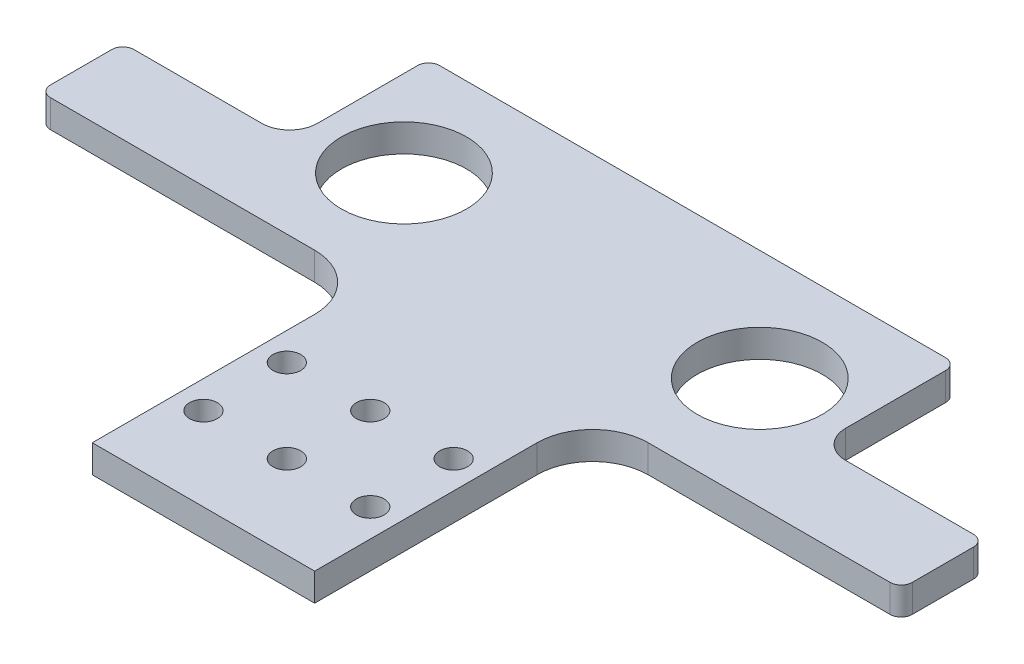
SolidWorks part; units mm, degrees
ref_plane "Front Plane" through (0, 0, 0) normal (0, 0, 1) x (1, 0, 0)
ref_plane "Top Plane" through (0, 0, 0) normal (0, 1, 0) x (1, 0, 0)
ref_plane "Right Plane" through (0, 0, 0) normal (1, 0, 0) x (0, 0, -1)
sketch "Sketch2" plane through (0, 0, 0) normal (0, 1, 0) x (1, 0, 0)
  line L1 (-52.4007, -9.869) -> (68.2493, -9.869)
  line L2 (-52.4007, -9.869) -> (-52.4007, 40.931)
  line L3 (-52.4007, 40.931) -> (68.2493, 40.931)
  line L4 (68.2493, -9.869) -> (68.2493, 40.931)
  line L5 (-52.4007, -9.869) -> (68.2493, 40.931) construction
  line L6 (-52.4007, 40.931) -> (68.2493, -9.869) construction
  point P0 (7.9243, 15.531)
  dimension "D1" = 120.65
  dimension "D2" = 50.8
extrude "Boss-Extrude1" add sketch "Sketch2" along normal blind 6.35
ref_plane "Plane1" through (7.9243, 0, 0) normal (1, 0, 0) x (0, 0, -1)
sketch "Sketch3" plane through (0, 6.35, 0) normal (0, 1, 0) x (1, 0, 0)
  line L0 (7.9243, -3.4925) -> (7.9243, 3.4925) construction
  line L2 (68.2493, 40.931) -> (-52.4007, 40.931) construction
  circle A0 centre (-32.7157, 15.6148) radius 14.2875
  dimension "D1" = 28.575
  dimension "D2" = 40.64
  dimension "D3" = 25.3163
extrude "Cut-Extrude1" cut sketch "Sketch3" against normal blind 6.35 contours A0
mirror "Mirror1" about plane through (7.9243, 0, 0) normal (1, 0, 0) of "Cut-Extrude1"
sketch "Sketch6" plane through (0, 6.35, 0) normal (0, 1, 0) x (1, 0, 0)
  line L0 (-52.4007, 40.931) -> (-52.4007, -9.869) construction
  line L1 (-90.5007, 9.181) -> (-52.4007, 9.181)
  line L2 (-90.5007, 9.181) -> (-90.5007, -9.869)
  line L3 (-90.5007, -9.869) -> (-52.4007, -9.869)
  line L4 (-52.4007, 9.181) -> (-52.4007, -9.869)
  line L5 (-52.4007, -9.869) -> (68.2493, -9.869) construction
  dimension "D1" = 38.1
  dimension "D2" = 0
  dimension "D3" = 0
  dimension "D4" = 19.05
extrude "Boss-Extrude2" add sketch "Sketch6" against normal blind 6.35
mirror "Mirror2" about plane through (7.9243, 0, 0) normal (1, 0, 0) of "Boss-Extrude2"
fillet "Fillet2" radius 6.35 2 edges at (68.2493, 3.175, -9.181) (-52.4007, 3.175, -9.181)
fillet "Fillet1" radius 2.54 6 edges at (68.2493, 3.175, -40.931) (-52.4007, 3.175, -40.931) (106.3493, 3.175, 9.869) (106.3493, 3.175, -9.181) (-90.5007, 3.175, 9.869) (-90.5007, 3.175, -9.181)
sketch "Sketch8" plane through (0, 6.35, 0) normal (0, 1, 0) x (1, 0, 0)
  line L0 (-87.9607, -9.869) -> (103.8093, -9.869) construction
  line L1 (-14.9357, -9.869) -> (35.8643, -9.869)
  line L2 (-14.9357, -9.869) -> (-14.9357, -73.369)
  line L3 (-14.9357, -73.369) -> (35.8643, -73.369)
  line L4 (35.8643, -9.869) -> (35.8643, -73.369)
  line L5 (106.3493, 6.641) -> (106.3493, -7.329) construction
  dimension "D1" = 50.8
  dimension "D2" = 63.5
  dimension "D3" = 70.485
extrude "Boss-Extrude3" add sketch "Sketch8" against normal blind 6.35 contours L3 L4 L1 L2
fillet "Fillet3" radius 12.7 2 edges at (35.8643, 3.175, 9.869) (-14.9357, 3.175, 9.869)
sketch "Sketch9" plane through (0, 6.35, 0) normal (0, 1, 0) x (1, 0, 0)
  line L0 (-14.9357, -22.569) -> (-14.9357, -73.369) construction
  line L1 (-14.9357, -73.369) -> (35.8643, -73.369) construction
  circle A0 centre (-8.5857, -54.319) radius 3.175
  dimension "D1" = 6.35
  dimension "D2" = 6.35
  dimension "D3" = 19.05
extrude "Cut-Extrude2" cut sketch "Sketch9" against normal blind 6.35
pattern_linear "LPattern1" count 3 spacing 19.05 along (1, 0, 0) count 2 spacing 19.05 along (0, 0, -1) of "Cut-Extrude2"
